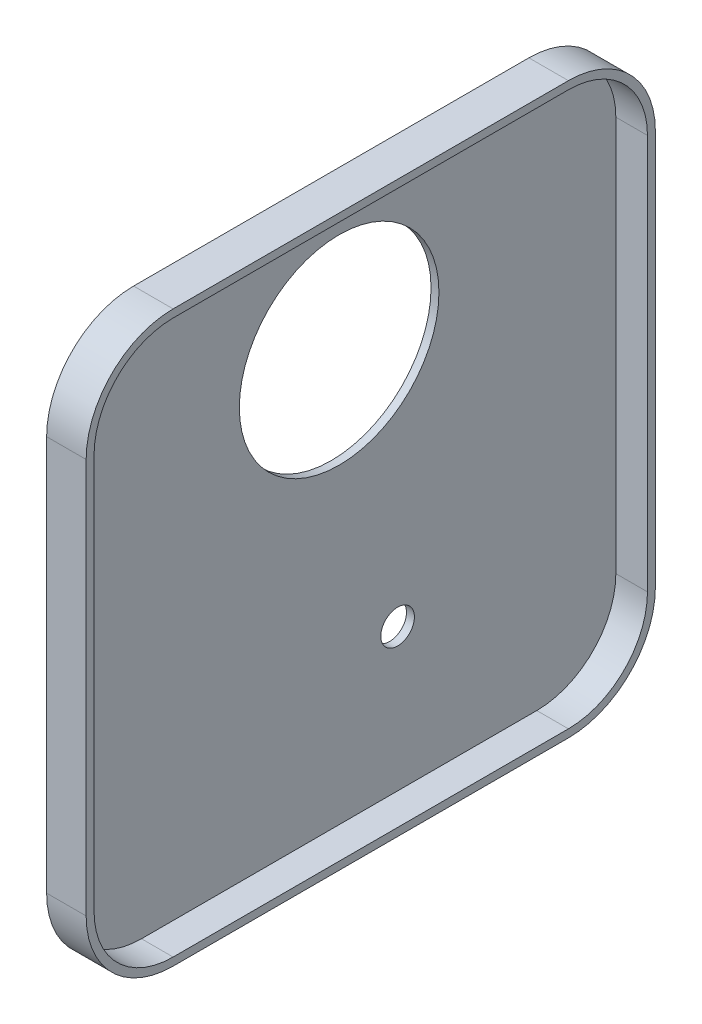
SolidWorks part; units mm, degrees
ref_plane "Front Plane" through (0, 0, 0) normal (1, 0, 0) x (0, 1, 0)
ref_plane "Top Plane" through (0, 0, 0) normal (0, 0, 1) x (0, 1, 0)
ref_plane "Right Plane" through (0, 0, 0) normal (0, 1, 0) x (-1, 0, 0)
sketch "Sketch1" plane through (0, 0, 0) normal (1, 0, 0) x (0, 1, 0)
  line L0 (-50, 72) -> (50, 72)
  line L1 (-50, -70) -> (50, -70) construction
  line L2 (-70, -50) -> (-70, 50) construction
  line L3 (-50, 70) -> (50, 70) construction
  line L4 (70, -50) -> (70, 50) construction
  line L5 (-70, -70) -> (70, 70) construction
  line L6 (-70, 70) -> (70, -70) construction
  line L7 (72, -50) -> (72, 50)
  line L8 (-50, -72) -> (50, -72)
  line L9 (-72, -50) -> (-72, 50)
  circle A1 centre (0, 0) radius 70 construction
  circle A2 centre (34, 0) radius 25.25
  circle A3 centre (-34, -14.79) radius 4.25
  arc A4 (50, -70) -> (70, -50) centre (50, -50) ccw construction
  arc A5 (-50, -70) -> (-70, -50) centre (-50, -50) cw construction
  arc A6 (-70, 50) -> (-50, 70) centre (-50, 50) cw construction
  arc A7 (50, 70) -> (70, 50) centre (50, 50) cw construction
  arc A8 (50, 72) -> (72, 50) centre (50, 50) cw
  arc A9 (50, -72) -> (72, -50) centre (50, -50) ccw
  arc A10 (-50, -72) -> (-72, -50) centre (-50, -50) cw
  arc A11 (-72, 50) -> (-50, 72) centre (-50, 50) cw
  dimension "D4" = 8.5
  dimension "D5" = 50.5
  dimension "D6" = 140
  dimension "D7" = 20
  dimension "D1" = 34
  dimension "D2" = 34
  dimension "D3" = 14.79
  dimension "D8" = 2
extrude "Boss-Extrude1" add sketch "Sketch1" along normal blind 10
shell "Shell1" thickness 2
sketch "Sketch2" plane through (2, 0, 0) normal (1, 0, 0) x (0, 1, 0)
  circle A0 centre (0, 0) radius 63.4006
  dimension "D1" = 126.8012
extrude "Cut-Extrude1" cut sketch "Sketch2" along normal blind 29
